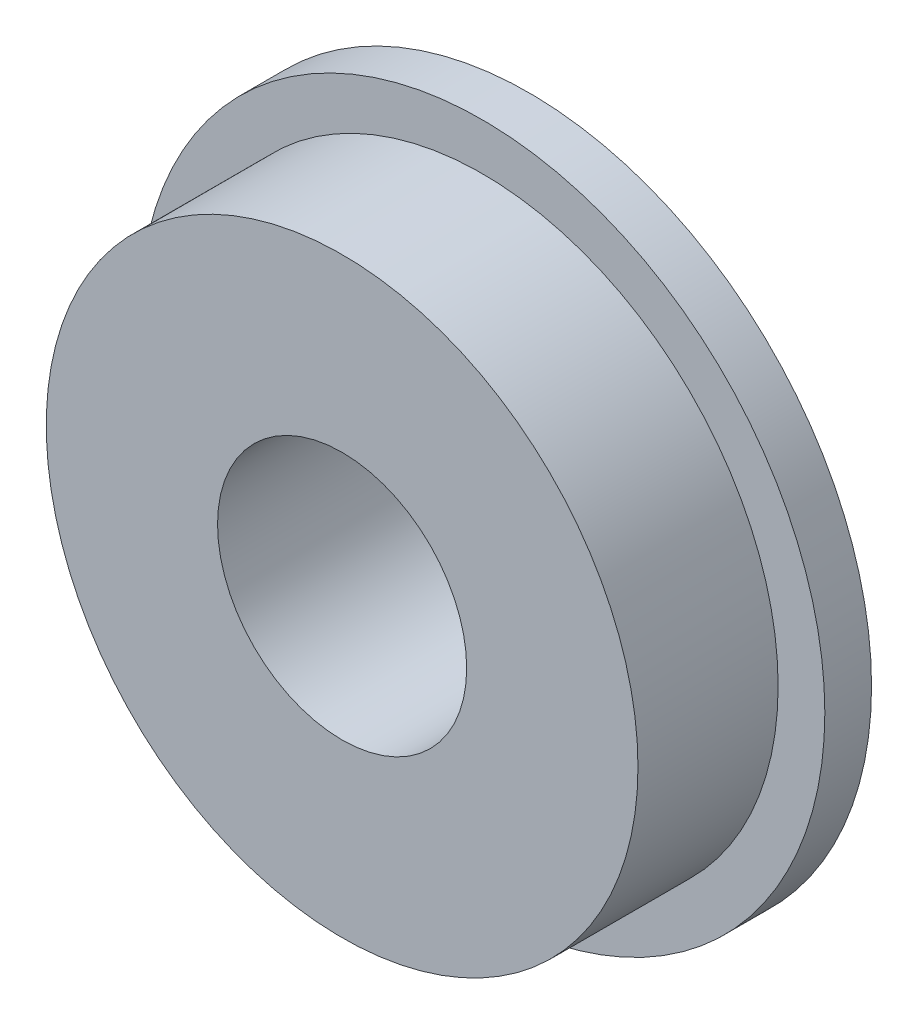
SolidWorks part; units mm, degrees
material "6061 合金"
ref_plane "前视基准面" through (0, 0, 0) normal (0, 0, 1) x (1, 0, 0)
ref_plane "上视基准面" through (0, 0, 0) normal (0, 1, 0) x (1, 0, 0)
ref_plane "右视基准面" through (0, 0, 0) normal (1, 0, 0) x (0, 0, -1)
sketch "草图1" plane through (0, 0, 0) normal (0, 0, 1) x (1, 0, 0)
  circle A0 centre (0, 0) radius 11
  dimension "D1" = 22
extrude "凸台-拉伸1" add sketch "草图1" along normal blind 1.5
sketch "草图2" plane through (0, 0, 1.5) normal (0, 0, 1) x (1, 0, 0)
  circle A0 centre (0, 0) radius 9.5
  dimension "D1" = 19
extrude "凸台-拉伸2" add sketch "草图2" along normal blind 4.5
sketch "草图3" plane through (0, 0, 6) normal (0, 0, 1) x (1, 0, 0)
  circle A0 centre (0, 0) radius 4
  dimension "D1" = 8
extrude "切除-拉伸1" cut sketch "草图3" against normal through all
